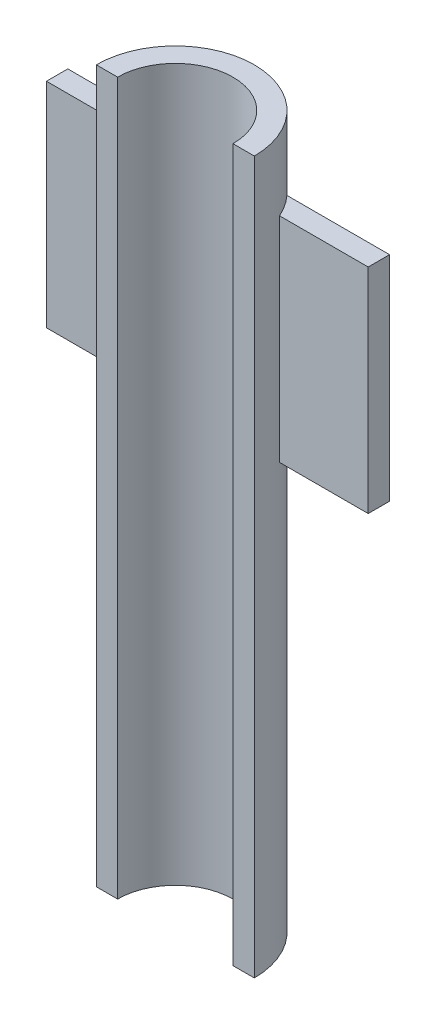
SolidWorks part; units mm, degrees
ref_plane "Front Plane" through (0, 0, 0) normal (0, 0, 1) x (1, 0, 0)
ref_plane "Top Plane" through (0, 0, 0) normal (0, 1, 0) x (1, 0, 0)
ref_plane "Right Plane" through (0, 0, 0) normal (1, 0, 0) x (0, 0, -1)
sketch "Sketch1" plane through (0, 0, 0) normal (0, 1, 0) x (1, 0, 0)
  circle A0 centre (0, 0) radius 8.1
  circle A1 centre (0, 0) radius 11.1
  dimension "D1" = 3
  dimension "D2" = 16.2
extrude "Boss-Extrude1" add sketch "Sketch1" along normal mid plane 100
sketch "Sketch2" plane through (0, -50, 0) normal (0, -1, 0) x (1, 0, 0)
  circle A0 centre (0, 0) radius 11.1
sketch "Sketch3" plane through (0, 0, 0) normal (0, 0, 1) x (1, 0, 0)
  line L1 (-101.5851, -102.8012) -> (101.5851, -102.8012)
  line L2 (-101.5851, -102.8012) -> (-101.5851, 102.8012)
  line L3 (-101.5851, 102.8012) -> (101.5851, 102.8012)
  line L4 (101.5851, -102.8012) -> (101.5851, 102.8012)
  line L5 (-101.5851, -102.8012) -> (101.5851, 102.8012) construction
  line L6 (-101.5851, 102.8012) -> (101.5851, -102.8012) construction
  point P0 (0, 0)
extrude "Cut-Extrude1" cut sketch "Sketch3" along normal through all
sketch "Sketch4" plane through (0, -50, 0) normal (0, -1, 0) x (1, 0, 0)
  circle A0 centre (0, 0) radius 11.1
ref_plane "Plane2" through (0, 0, -6) normal (0, 0, 1) x (1, 0, 0)
sketch "Sketch6" plane through (0, 0, -6) normal (0, 0, 1) x (1, 0, 0)
  line L0 (0, 17.3633) -> (0, 69.1455) construction
  line L1 (11.1, 50) -> (8.1, 50) construction
  line L2 (7.6, 40) -> (22.6, 40)
  line L3 (7.6, 40) -> (7.6, 10)
  line L4 (7.6, 10) -> (22.6, 10)
  line L5 (22.6, 40) -> (22.6, 10)
  line L7 (-22.6, 40) -> (-22.6, 10)
  line L8 (-7.6, 10) -> (-22.6, 10)
  line L9 (-7.6, 40) -> (-7.6, 10)
  line L10 (-7.6, 40) -> (-22.6, 40)
  dimension "D1" = 10
  dimension "D2" = 30
  dimension "D3" = 7.6
  dimension "D4" = 15
extrude "Boss-Extrude4" add sketch "Sketch6" along normal mid plane 3
sketch "Sketch7" plane through (0, 0, -7.5) normal (0, 0, -1) x (-1, 0, 0)
  line L0 (15.3915, 40) -> (15.3915, 10) construction
  line L1 (8.1829, 40) -> (22.6, 40) construction
  line L2 (22.6, 10) -> (8.1829, 10) construction
  line L3 (0, 0) -> (0, 47.416) construction
  text T0 "A2N\r\n3mm mold" font "Century Gothic" height in points 11
extrude "Boss-Extrude5" add sketch "Sketch7" along normal blind 1.5
